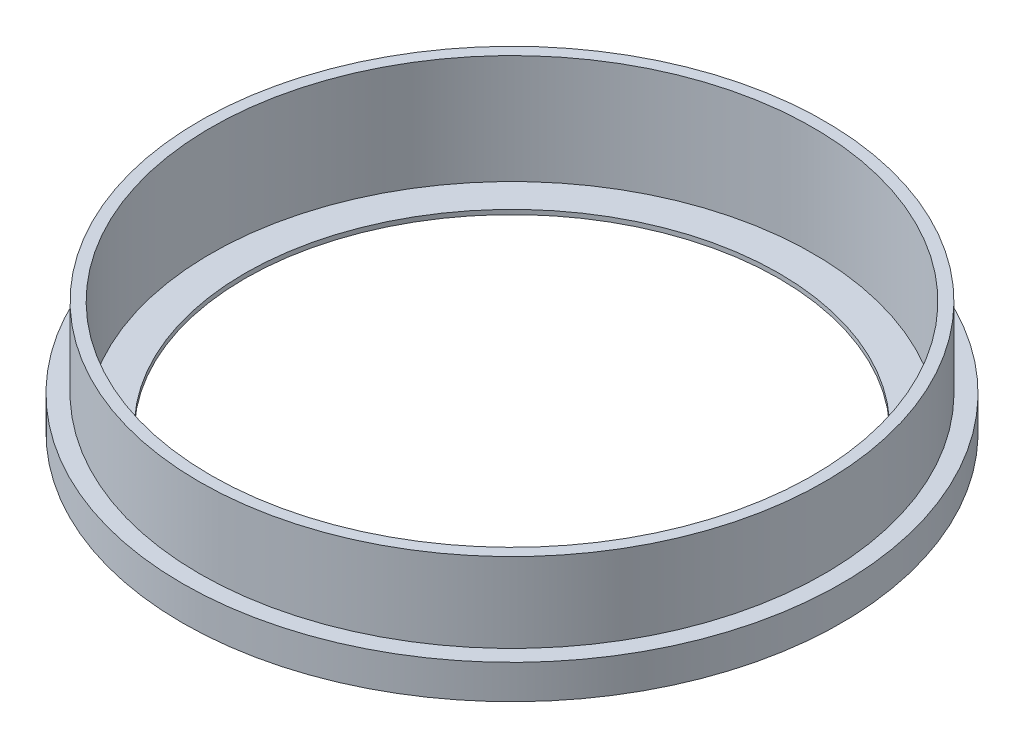
SolidWorks part; units mm, degrees
ref_plane "Front Plane" through (0, 0, 0) normal (0, 0, 1) x (1, 0, 0)
ref_plane "Top Plane" through (0, 0, 0) normal (0, 1, 0) x (1, 0, 0)
ref_plane "Right Plane" through (0, 0, 0) normal (1, 0, 0) x (0, 0, -1)
sketch "Sketch1" plane through (0, 0, 0) normal (0, 1, 0) x (1, 0, 0)
  circle A0 centre (0, 0) radius 27.5
  dimension "D1" = 55
extrude "Boss-Extrude1" add sketch "Sketch1" along normal blind 10
sketch "Sketch2" plane through (0, 0, 0) normal (0, 1, 0) x (1, 0, 0)
  circle A0 centre (0, 0) radius 29
  dimension "D1" = 58
extrude "Extrude-Thin1" add sketch "Sketch2" along normal blind 3 thin thin type one direction reverse wall 5
sketch "Sketch3" plane through (0, 10, 0) normal (0, 1, 0) x (1, 0, 0)
  circle A0 centre (0, 0) radius 26.5
  dimension "D1" = 53
extrude "Cut-Extrude1" cut sketch "Sketch3" against normal blind 9.6
sketch "Sketch4" plane through (0, 0.4, 0) normal (0, 1, 0) x (1, 0, 0)
  circle A0 centre (0, 0) radius 23.5
  circle A1 centre (0, 0) radius 26.5 construction
  dimension "D1" = 3
extrude "Cut-Extrude2" cut sketch "Sketch4" against normal through all
